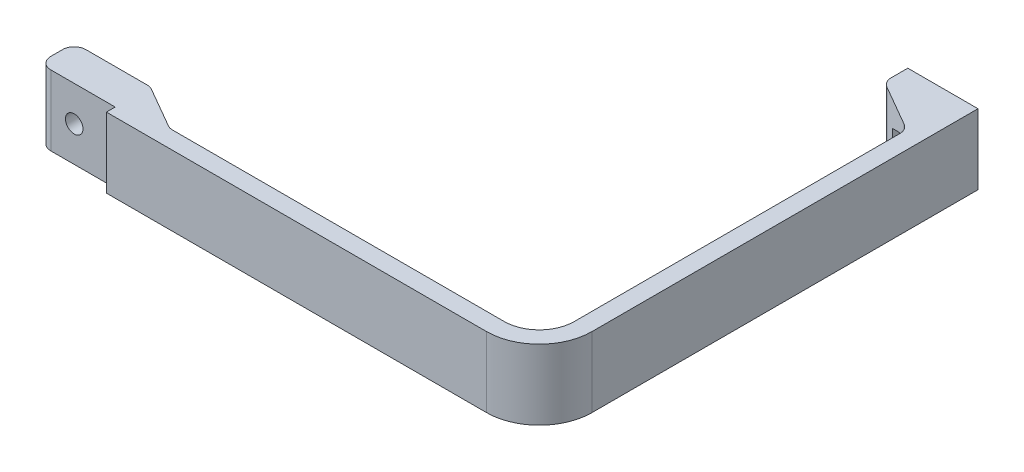
SolidWorks part; units mm, degrees
material "ABS"
ref_plane "Front" through (0, 0, 0) normal (0, 0, 1) x (1, 0, 0)
ref_plane "Top" through (0, 0, 0) normal (0, 1, 0) x (1, 0, 0)
ref_plane "Right" through (0, 0, 0) normal (1, 0, 0) x (0, 0, -1)
sketch "Esquisse1" plane through (0, 0, 0) normal (0, 1, 0) x (1, 0, 0)
  line L0 (-12, 0) -> (0, 0)
  line L1 (0, 0) -> (0, -66)
  line L2 (-9, -75) -> (-74, -75)
  line L3 (-74, -75) -> (-74, -73.5)
  line L4 (-74, -73.5) -> (-87, -73.5)
  line L5 (-87, -73.5) -> (-87, -67.5)
  line L6 (-87, -67.5) -> (-74, -67.5)
  line L7 (-74, -67.5) -> (-66.2058, -72)
  line L8 (-66.2058, -72) -> (-9, -72)
  line L9 (-3, -66) -> (-3, -9.1962)
  line L10 (-3, -9.1962) -> (-12, -4)
  line L11 (-12, -4) -> (-12, 0)
  arc A0 (0, -66) -> (-9, -75) centre (-9, -66) cw
  arc A1 (-9, -72) -> (-3, -66) centre (-9, -66) ccw
  point P20 (-74, -74.25)
  dimension "D1" = 75
  dimension "D11" = 9
  dimension "D2" = 87
  dimension "D3" = 3
  dimension "D4" = 4
  dimension "D5" = 12
  dimension "D6" = 60
  dimension "D7" = 30
  dimension "D8" = 1.5
  dimension "D9" = 6
  dimension "D10" = 13
extrude "Boss.-Extru.1" add sketch "Esquisse1" along normal mid plane 12
sketch "Esquisse2" plane through (0, 0, 0) normal (0, 0, -1) x (-1, 0, 0)
  line L0 (0, 6) -> (12, 6) construction
  line L1 (50, 0) -> (-50, 0) construction
  circle A0 centre (6, 0) radius 1.5
  point P4 (6, 6)
  dimension "D1" = 3
extrude "Enlèv. mat.-Extru.1" cut sketch "Esquisse2" against normal blind 12
sketch "Esquisse3" plane through (0, 0, 67.5) normal (0, 0, -1) x (-1, 0, 0)
  line L0 (87, 6) -> (87, -6) construction
  circle A0 centre (81, 0) radius 1.5
  circle A1 centre (6, 0) radius 1.5 construction
  dimension "D1" = 6
extrude "Enlèv. mat.-Extru.2" cut sketch "Esquisse3" against normal blind 12
fillet "Congé1" radius 2 6 edges at (-87, 0, 73.5) (-87, 0, 67.5) (-74, 0, 67.5) (-66.2058, 0, 72) (-12, 0, 4) (-3, 0, 9.1962)
sketch "Esquisse4" plane through (0, 0, 67.5) normal (0, 0, -1) x (-1, 0, 0)
  line L1 (83.8, 1.6166) -> (81, 3.2332)
  line L2 (81, 3.2332) -> (78.2, 1.6166)
  line L3 (78.2, 1.6166) -> (78.2, -1.6166)
  line L4 (78.2, -1.6166) -> (81, -3.2332)
  line L5 (81, -3.2332) -> (83.8, -1.6166)
  line L6 (83.8, -1.6166) -> (83.8, 1.6166)
  circle A0 centre (81, 0) radius 2.8 construction
  dimension "D1" = 5.6
extrude "Enlèv. mat.-Extru.3" cut sketch "Esquisse4" against normal blind 3
sketch "Esquisse5" plane through (0, 0, 0) normal (0, 0, -1) x (-1, 0, 0)
  line L1 (8.8, 1.6166) -> (6, 3.2332)
  line L2 (6, 3.2332) -> (3.2, 1.6166)
  line L3 (3.2, 1.6166) -> (3.2, -1.6166)
  line L4 (3.2, -1.6166) -> (6, -3.2332)
  line L5 (6, -3.2332) -> (8.8, -1.6166)
  line L6 (8.8, -1.6166) -> (8.8, 1.6166)
  circle A0 centre (6, 0) radius 2.8 construction
  dimension "D1" = 5.6
extrude "Enlèv. mat.-Extru.4" cut sketch "Esquisse5" against normal blind 10 from offset 3
